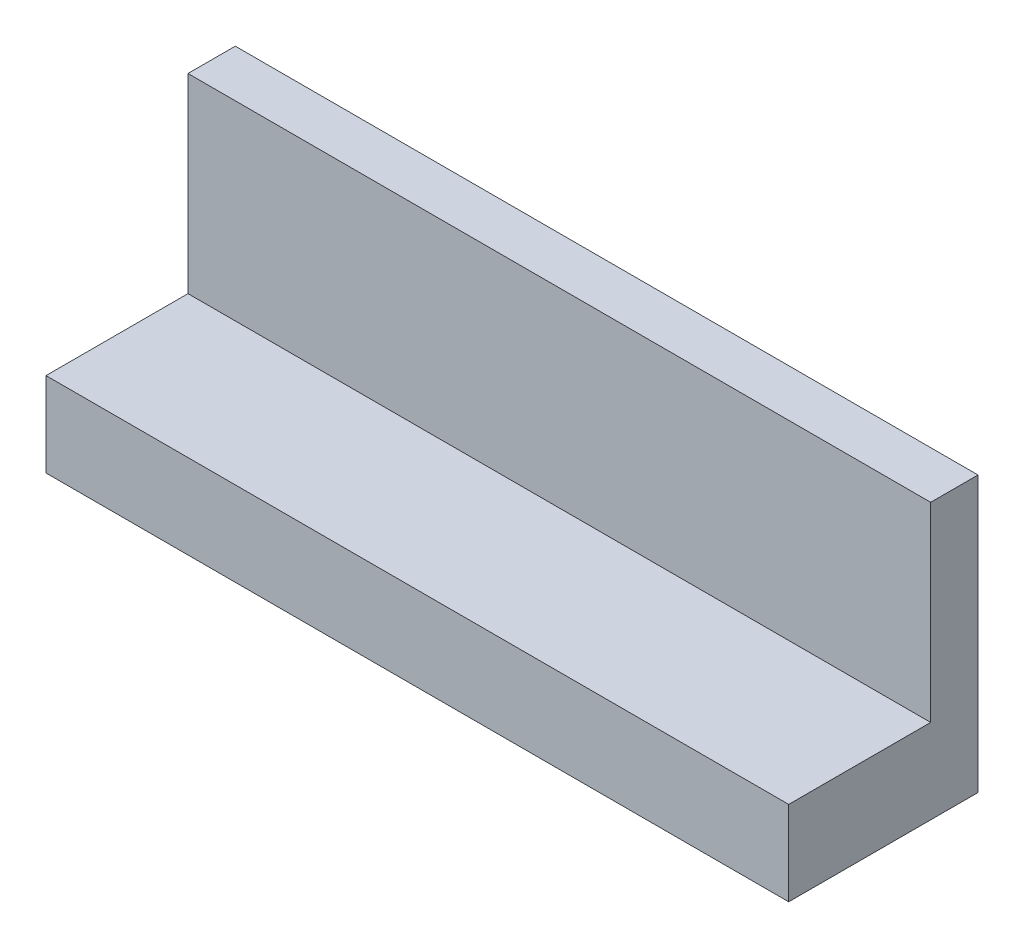
SolidWorks part; units mm, degrees
ref_plane "前视基准面" through (0, 0, 0) normal (0, 0, 1) x (1, 0, 0)
ref_plane "上视基准面" through (0, 0, 0) normal (0, 1, 0) x (1, 0, 0)
ref_plane "右视基准面" through (0, 0, 0) normal (1, 0, 0) x (0, 0, -1)
other "Configuration Table"
sketch "草图1" plane through (0, 0, 0) normal (0, 0, 1) x (1, 0, 0)
  line L1 (-78.4735, -29.0593) -> (78.4735, -29.0593)
  line L2 (-78.4735, -29.0593) -> (-78.4735, 29.0593)
  line L3 (-78.4735, 29.0593) -> (78.4735, 29.0593)
  line L4 (78.4735, -29.0593) -> (78.4735, 29.0593)
  line L5 (-78.4735, -29.0593) -> (78.4735, 29.0593) construction
  line L6 (-78.4735, 29.0593) -> (78.4735, -29.0593) construction
  point P0 (0, 0)
extrude "凸台-拉伸1" add sketch "草图1" along normal mid plane 10
sketch "草图2" plane through (0, 0, 5) normal (0, 0, 1) x (1, 0, 0)
  line L1 (-78.4735, -11.2269) -> (78.4735, -11.2269)
  line L2 (-78.4735, -11.2269) -> (-78.4735, -29.0593)
  line L3 (-78.4735, -29.0593) -> (78.4735, -29.0593)
  line L4 (78.4735, -11.2269) -> (78.4735, -29.0593)
  line L5 (-78.4735, -11.2269) -> (78.4735, -29.0593) construction
  line L6 (-78.4735, -29.0593) -> (78.4735, -11.2269) construction
  point P0 (0, -20.1431)
extrude "凸台-拉伸2" add sketch "草图2" along normal blind 30
